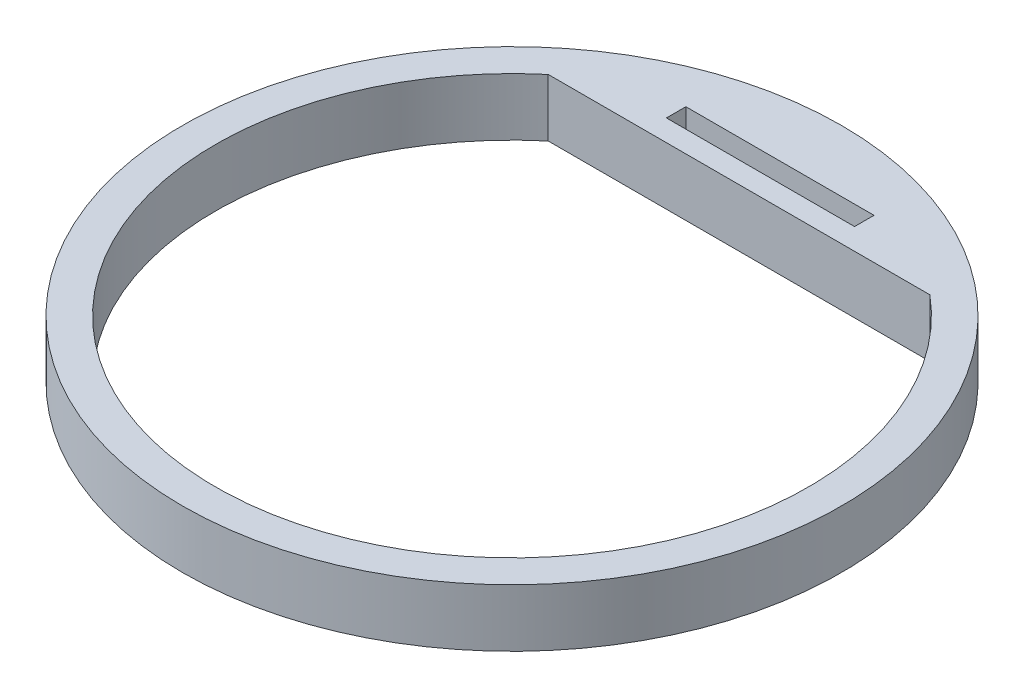
SolidWorks part; units mm, degrees
ref_plane "Front Plane" through (0, 0, 0) normal (0, 0, 1) x (1, 0, 0)
ref_plane "Top Plane" through (0, 0, 0) normal (0, 1, 0) x (1, 0, 0)
ref_plane "Right Plane" through (0, 0, 0) normal (1, 0, 0) x (0, 0, -1)
sketch "Sketch1" plane through (0, 0, 0) normal (0, 1, 0) x (1, 0, 0)
  line L0 (0, 0) -> (0, 35) construction
  line L1 (29.4163, 35) -> (-29.4163, 35)
  circle A0 centre (0, 0) radius 50.8
  circle A1 centre (0, 0) radius 45.72
  point P8 (0, 35)
  dimension "D1" = 101.6
  dimension "D2" = 91.44
  dimension "D3" = 35
extrude "Boss-Extrude1" add sketch "Sketch1" along normal blind 8.89 contours A0 A1 | L1 A1
sketch "Sketch2" plane through (0, 8.89, 0) normal (0, 1, 0) x (1, 0, 0)
  line L0 (0, 50.8) -> (0, 41.3) construction
  line L1 (-14.5, 41.3) -> (14.5, 41.3)
  line L2 (14.5, 41.3) -> (14.5, 38.3)
  line L3 (14.5, 38.3) -> (-14.5, 38.3)
  line L4 (-14.5, 41.3) -> (-14.5, 38.3)
  circle A0 centre (0, 0) radius 50.8 construction
  point P9 (0, 38.3)
  dimension "D1" = 9.5
  dimension "D2" = 14.5
  dimension "D3" = 3
extrude "Cut-Extrude2" cut sketch "Sketch2" against normal blind 127
